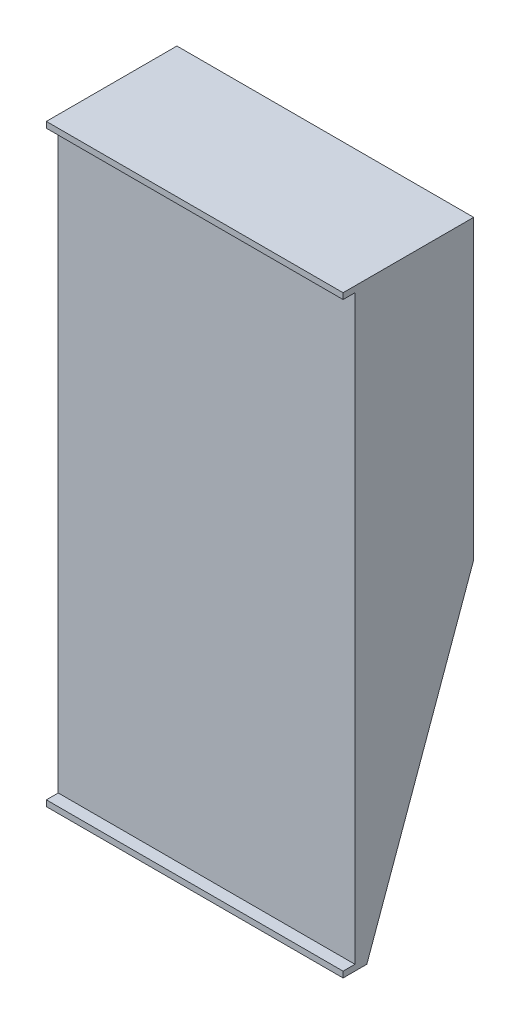
SolidWorks part; units mm, degrees
material "AISI 304"
ref_plane "Front Plane" through (0, 0, 0) normal (0, 0, 1) x (1, 0, 0)
ref_plane "Top Plane" through (0, 0, 0) normal (0, 1, 0) x (1, 0, 0)
ref_plane "Right Plane" through (0, 0, 0) normal (1, 0, 0) x (0, 0, -1)
sketch "Sketch1" plane through (0, 0, 0) normal (0, 0, 1) x (1, 0, 0)
  line L1 (-3.175, -6.35) -> (3.175, -6.35)
  line L2 (-3.175, -6.35) -> (-3.175, 6.35)
  line L3 (-3.175, 6.35) -> (3.175, 6.35)
  line L4 (3.175, -6.35) -> (3.175, 6.35)
  line L5 (-3.175, -6.35) -> (3.175, 6.35) construction
  line L6 (-3.175, 6.35) -> (3.175, -6.35) construction
  point P0 (0, 0)
  dimension "D1" = 12.7
  dimension "D2" = 6.35
extrude "Boss-Extrude1" add sketch "Sketch1" along normal blind 2.54
sketch "Sketch2" plane through (0, 0, 2.54) normal (0, 0, 1) x (1, 0, 0)
  line L0 (3.175, -6.35) -> (3.175, 6.35) construction
  line L1 (-3.175, -6.35) -> (3.175, -6.35)
  line L2 (-3.175, -6.35) -> (-3.175, -6.223)
  line L3 (-3.175, -6.223) -> (3.175, -6.223)
  line L4 (3.175, -6.35) -> (3.175, -6.223)
  dimension "D1" = 0.127
extrude "Boss-Extrude2" add sketch "Sketch2" along normal blind 0.254
mirror "Mirror1" about plane through (0, 0, 0) normal (0, 1, 0) of "Boss-Extrude2"
sketch "Sketch3" plane through (3.175, 0, 0) normal (1, 0, 0) x (0, 0, -1)
  line L0 (0, -6.35) -> (-2.286, -6.35)
  line L1 (-2.794, -6.35) -> (0, -6.35) construction
  line L2 (-2.286, -6.35) -> (0, 0)
  line L3 (0, 0) -> (0, -6.35)
  line L4 (-2.794, -6.35) -> (-2.794, -6.223) construction
  dimension "D1" = 0.508
extrude "Cut-Extrude1" cut sketch "Sketch3" against normal through all
